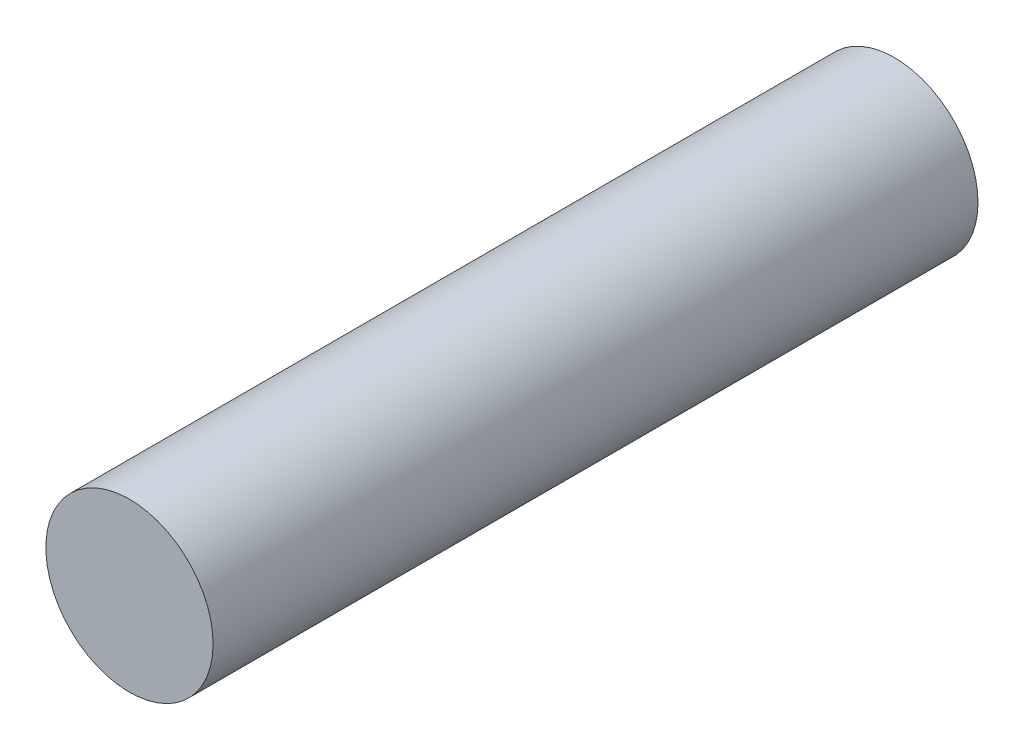
SolidWorks part; units mm, degrees
ref_plane "前视基准面" through (0, 0, 0) normal (0, 0, 1) x (1, 0, 0)
ref_plane "上视基准面" through (0, 0, 0) normal (0, 1, 0) x (1, 0, 0)
ref_plane "右视基准面" through (0, 0, 0) normal (1, 0, 0) x (0, 0, -1)
sketch "草图1" plane through (0, 0, 0) normal (0, 0, 1) x (1, 0, 0)
  circle A0 centre (0, 0) radius 3.2796
  dimension "D1" = 6.5592
extrude "凸台-拉伸1" add sketch "草图1" along normal blind 30
